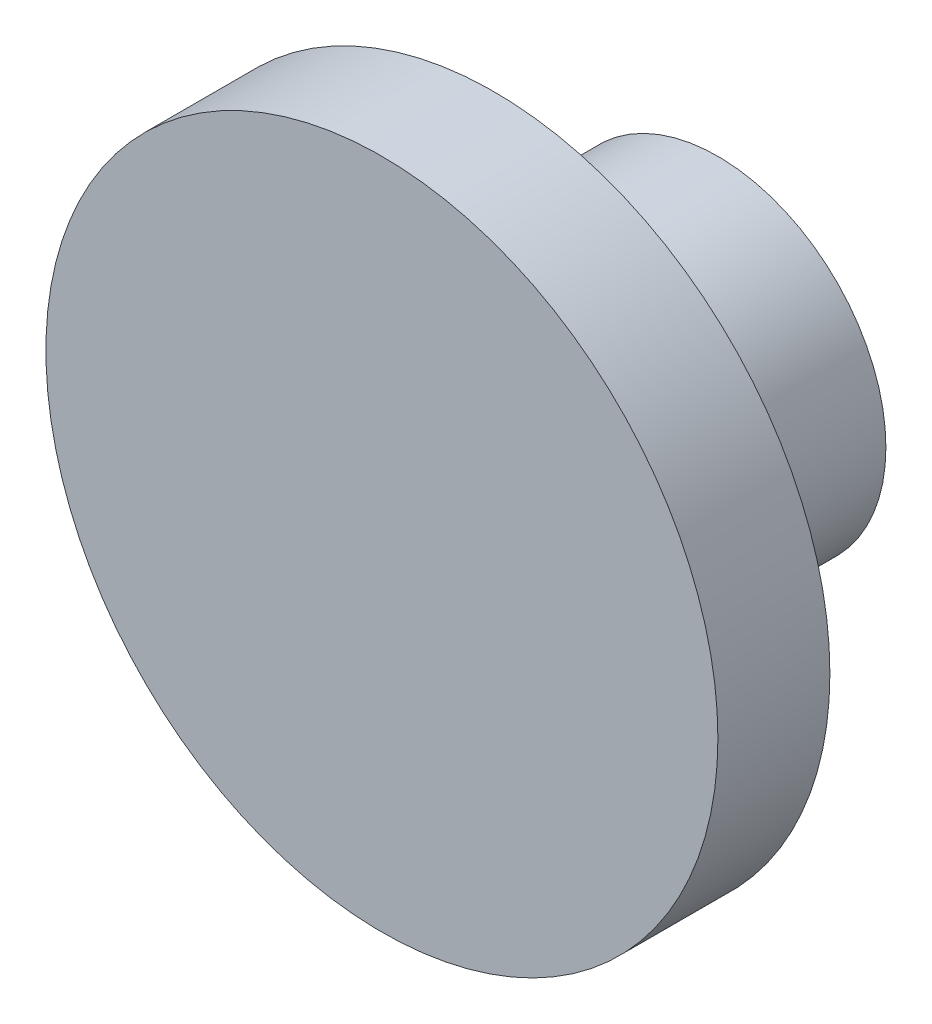
SolidWorks part; units mm, degrees
ref_plane "Front Plane" through (0, 0, 0) normal (0, 0, 1) x (1, 0, 0)
ref_plane "Top Plane" through (0, 0, 0) normal (0, 1, 0) x (1, 0, 0)
ref_plane "Right Plane" through (0, 0, 0) normal (1, 0, 0) x (0, 0, -1)
sketch "Sketch1" plane through (0, 0, 0) normal (0, 0, 1) x (1, 0, 0)
  circle A0 centre (0, 0) radius 7.5
  dimension "D1" = 15
extrude "Boss-Extrude1" add sketch "Sketch1" along normal blind 10
sketch "Sketch2" plane through (0, 0, 10) normal (0, 0, 1) x (1, 0, 0)
  circle A0 centre (0, 0) radius 15
  circle A1 centre (0, 0) radius 7.5 construction
  dimension "D1" = 30
extrude "Boss-Extrude2" add sketch "Sketch2" along normal blind 5
sketch "Sketch3" plane through (0, 0, 0) normal (0, 0, -1) x (-1, 0, 0)
  circle A0 centre (0, 0) radius 2.5
  dimension "D1" = 5
extrude "Cut-Extrude1" cut sketch "Sketch3" against normal blind 5
